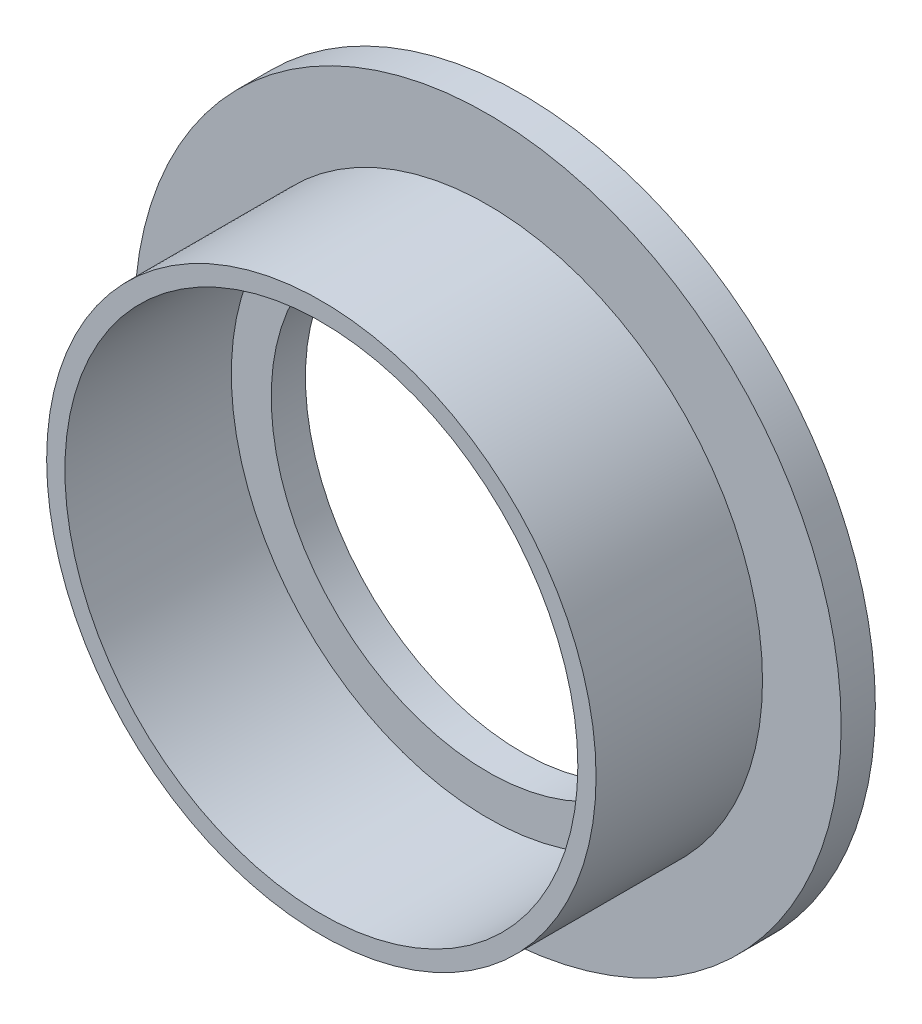
SolidWorks part; units mm, degrees
ref_plane "Alzado" through (0, 0, 0) normal (0, 0, 1) x (1, 0, 0)
ref_plane "Planta" through (0, 0, 0) normal (0, 1, 0) x (1, 0, 0)
ref_plane "Vista lateral" through (0, 0, 0) normal (1, 0, 0) x (0, 0, -1)
sketch "Croquis1" plane through (0, 0, 0) normal (0, 0, 1) x (1, 0, 0)
  circle A0 centre (0, 0) radius 9.5
  circle A1 centre (0, 0) radius 15.5
  dimension "D1" = 19
  dimension "D2" = 31
extrude "Saliente-Extruir1" add sketch "Croquis1" along normal blind 1.5
sketch "Croquis2" plane through (0, 0, 1.5) normal (0, 0, 1) x (1, 0, 0)
  circle A0 centre (0, 0) radius 11.25
  circle A1 centre (0, 0) radius 12.05
  dimension "D1" = 22.5
  dimension "D2" = 24.1
extrude "Saliente-Extruir2" add sketch "Croquis2" along normal blind 7.3
